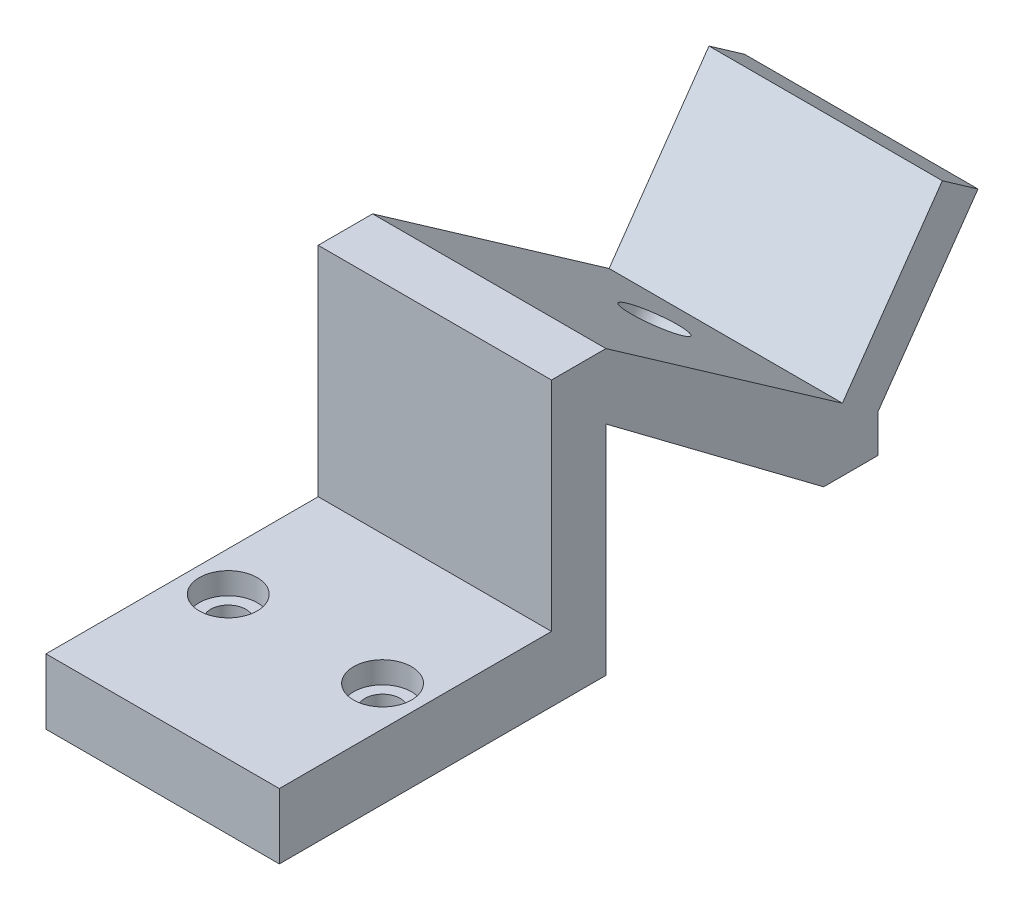
SolidWorks part; units mm, degrees
ref_plane "Front Plane" through (0, 0, 0) normal (0, 0, 1) x (1, 0, 0)
ref_plane "Top Plane" through (0, 0, 0) normal (0, 1, 0) x (1, 0, 0)
ref_plane "Right Plane" through (0, 0, 0) normal (1, 0, 0) x (0, 0, -1)
sketch "Sketch1" plane through (0, 0, 0) normal (0, 1, 0) x (1, 0, 0)
  line L1 (-13.9568, 42.3827) -> (13.2632, 42.3827)
  line L2 (-13.9568, 42.3827) -> (-13.9568, -8.4173)
  line L3 (-13.9568, -8.4173) -> (13.2632, -8.4173)
  line L4 (13.2632, 42.3827) -> (13.2632, -8.4173)
  dimension "D1" = 50.8
  dimension "D2" = 27.22
extrude "Boss-Extrude1" add sketch "Sketch1" along normal blind 7.62
sketch "Sketch2" plane through (0, 7.62, 0) normal (0, 1, 0) x (1, 0, 0)
  line L0 (-13.9568, 42.3827) -> (-13.9568, -8.4173) construction
  line L1 (-13.9568, -8.4173) -> (13.2632, -8.4173) construction
  circle A0 centre (-9.3468, 8.2327) radius 2.05
  point P0 (-9.3468, 8.2327)
  dimension "D1" = 4.61
  dimension "D2" = 16.65
extrude "Cut-Extrude1" cut sketch "Sketch2" against normal blind 7.62 contours A0
sketch "Sketch3" plane through (0, 7.62, 0) normal (0, 1, 0) x (1, 0, 0)
  circle A0 centre (-9.3468, 8.2327) radius 3.3782
  point P0 (-9.3468, 8.2327)
extrude "Cut-Extrude2" cut sketch "Sketch3" against normal blind 2.54
ref_plane "Plane1" through (-0.3468, 0, 0) normal (-1, 0, 0) x (0, 0, 1)
mirror "Mirror1" about plane through (-0.3468, 0, 0) normal (-1, 0, 0) of "Cut-Extrude2", "Cut-Extrude1"
sketch "Sketch4" plane through (0, 7.62, 0) normal (0, 1, 0) x (1, 0, 0)
  line L0 (13.2632, -8.4173) -> (13.2632, 42.3827) construction
  line L1 (-13.9568, 42.3827) -> (13.2632, 42.3827)
  line L2 (-13.9568, 42.3827) -> (-13.9568, 23.3327)
  line L3 (-13.9568, 23.3327) -> (13.2632, 23.3327)
  line L4 (13.2632, 42.3827) -> (13.2632, 23.3327)
  dimension "D1" = 19.05
extrude "Boss-Extrude2" add sketch "Sketch4" along normal blind 25.4
sketch "Sketch5" plane through (0, 0, -42.3827) normal (0, 0, -1) x (-1, 0, 0)
  line L1 (-13.2632, 0) -> (13.9568, 0)
  line L2 (-13.2632, 0) -> (-13.2632, 33.02)
  line L3 (-13.2632, 33.02) -> (13.9568, 33.02)
  line L4 (13.9568, 0) -> (13.9568, 33.02)
extrude "Boss-Extrude3" add sketch "Sketch5" along normal blind 25.4
sketch "Sketch7" plane through (0, 0, -67.7827) normal (0, 0, -1) x (-1, 0, 0)
  line L0 (-13.2632, 33.02) -> (-13.2632, 0) construction
  line L1 (13.9568, 0) -> (-13.2632, 0)
  line L2 (13.9568, 0) -> (13.9568, 6.35)
  line L3 (13.9568, 6.35) -> (-13.2632, 6.35)
  line L4 (-13.2632, 0) -> (-13.2632, 6.35)
  dimension "D1" = 6.35
extrude "Cut-Extrude3" cut sketch "Sketch7" against normal blind 38.1
sketch "Sketch8" plane through (-13.9568, 0, 0) normal (-1, 0, 0) x (0, 0, 1)
  line L0 (-29.6827, 6.35) -> (-29.6827, 25.4)
  line L1 (-29.6827, 25.4) -> (-55.0827, 6.35)
  line L2 (-29.6827, 6.35) -> (-67.7827, 6.35) construction
  line L3 (-55.0827, 6.35) -> (-29.6827, 6.35)
  line L4 (-67.7827, 33.02) -> (-23.3327, 33.02) construction
  point P8 (0, 0)
  dimension "D1" = 7.62
  dimension "D2" = 12.7
extrude "Cut-Extrude4" cut sketch "Sketch8" against normal blind 27.94
sketch "Sketch9" plane through (-13.9568, 0, 0) normal (-1, 0, 0) x (0, 0, 1)
  line L0 (-67.7827, 33.02) -> (-67.7827, 6.35)
  line L1 (-67.7827, 6.35) -> (-29.6827, 33.02)
  line L2 (-67.7827, 33.02) -> (-23.3327, 33.02) construction
  line L3 (-29.6827, 33.02) -> (-67.7827, 33.02)
  dimension "D1" = 6.35
extrude "Cut-Extrude5" cut sketch "Sketch9" against normal blind 27.94
sketch "Sketch11" plane through (-13.9568, 0, 0) normal (-1, 0, 0) x (0, 0, 1)
  line L0 (-61.4327, 6.35) -> (-61.4327, 10.795)
  line L1 (-55.0827, 6.35) -> (-67.7827, 6.35) construction
  line L2 (-67.7827, 6.35) -> (-29.6827, 33.02) construction
  line L3 (-61.4327, 10.795) -> (-67.7827, 6.35)
  line L4 (-67.7827, 6.35) -> (-61.4327, 6.35)
extrude "Cut-Extrude6" cut sketch "Sketch11" against normal blind 27.94
sketch "Sketch12" plane through (0, 36.106, -25.2742) normal (0, 0.8192, -0.5735) x (1, 0, 0)
  line L0 (13.2632, 44.1371) -> (13.2632, 5.3813) construction
  line L1 (-13.9568, 44.1371) -> (13.2632, 44.1371)
  line L2 (-13.9568, 44.1371) -> (-13.9568, 39.0571)
  line L3 (-13.9568, 39.0571) -> (13.2632, 39.0571)
  line L4 (13.2632, 44.1371) -> (13.2632, 39.0571)
  dimension "D1" = 5.08
extrude "Boss-Extrude5" add sketch "Sketch12" along normal blind 20.32
sketch "Sketch15" plane through (0, 36.106, -25.2742) normal (0, 0.8192, -0.5735) x (1, 0, 0)
  line L0 (-0.3468, 39.0571) -> (-0.3468, 5.3813)
  line L1 (-13.9568, 39.0571) -> (13.2632, 39.0571) construction
  line L2 (13.2632, 5.3813) -> (-13.9568, 5.3813) construction
  circle A0 centre (-0.3468, 28.8971) radius 3.302
  dimension "D1" = 10.16
extrude "Cut-Extrude8" cut sketch "Sketch15" against normal blind 12.7 contours L0 A0 | L0 A0
sketch "Sketch16" plane through (0, 30.5037, -22.8778) normal (0, -0.8, 0.6) x (1, 0, 0)
  circle A0 centre (-0.3468, -27.6625) radius 4.826
extrude "Cut-Extrude9" cut sketch "Sketch16" against normal blind 2.54
